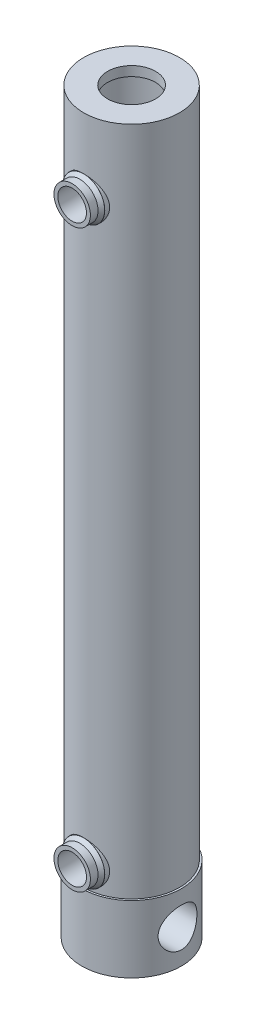
SolidWorks part; units mm, degrees
ref_plane "Plan de face" through (0, 0, 0) normal (0, 0, 1) x (1, 0, 0)
ref_plane "Plan de dessus" through (0, 0, 0) normal (0, 1, 0) x (1, 0, 0)
ref_plane "Plan de droite" through (0, 0, 0) normal (1, 0, 0) x (0, 0, -1)
sketch "Esquisse1" plane through (0, 0, 0) normal (0, 0, 1) x (1, 0, 0)
  line L0 (0, 0) -> (25, 0)
  line L1 (25, 0) -> (25, 350)
  line L2 (25, 350) -> (12.5, 350)
  line L3 (12.5, 350) -> (12.5, 345)
  line L4 (12.5, 345) -> (20, 345)
  line L5 (20, 345) -> (20, 3)
  line L6 (20, 3) -> (0, 3)
  line L7 (0, 3) -> (0, 0)
  line L8 (0, 3) -> (0, 350) construction
  line L9 (0, 350) -> (12.5, 350) construction
  dimension "D1" = 25
  dimension "D2" = 20
  dimension "D3" = 3
  dimension "D4" = 5
  dimension "D5" = 12.5
  dimension "D6" = 350
revolve "Révolution1" add sketch "Esquisse1" angle 360 about L8
sketch "Esquisse2" plane through (0, 0, 0) normal (0, -1, 0) x (-1, 0, 0)
  circle A0 centre (0, 0) radius 26
  dimension "D1" = 52
extrude "Boss.-Extru.1" add sketch "Esquisse2" along normal blind 35
sketch "Esquisse3" plane through (0, 0, 0) normal (0, 0, 1) x (1, 0, 0)
  line L0 (0, -17.5) -> (0, 0) construction
  line L1 (0, 0) -> (0, 311.5) construction
  circle A0 centre (0, -17.5) radius 10.125 construction
  circle A1 centre (0, 11.5) radius 7.475
  circle A2 centre (0, 311.5) radius 7.475
  dimension "D1" = 20.25
  dimension "D2" = 17.5
  dimension "D3" = 14.95
  dimension "D4" = 14.95
  dimension "D5" = 29
  dimension "D6" = 300
extrude "Enlèv. mat.-Extru.2" cut sketch "Esquisse3" along normal through all
sketch "Esquisse4" plane through (0, 0, 0) normal (1, 0, 0) x (0, 0, -1)
  circle A0 centre (0, -17.5) radius 10.125
  dimension "D1" = 20.25
extrude "Enlèv. mat.-Extru.3" cut sketch "Esquisse4" against normal through all both and the other way through all
ref_plane "Plan1" through (0, 0, 25) normal (0, 0, 1) x (1, 0, 0)
sketch "Esquisse5" plane through (0, 0, 25) normal (0, 0, 1) x (1, 0, 0)
  circle A0 centre (0, 311.5) radius 11
  circle A1 centre (0, 11.5) radius 11
  circle A2 centre (0, 311.5) radius 7.475
  circle A3 centre (0, 11.5) radius 7.475
  dimension "D1" = 22
  dimension "D2" = 22
extrude "Boss.-Extru.2" add sketch "Esquisse5" against normal up to next
sketch "Esquisse6" plane through (0, 0, 25) normal (0, 0, 1) x (1, 0, 0)
  circle A0 centre (0, 311.5) radius 7.475
  circle A1 centre (0, 311.5) radius 9.5
  circle A2 centre (0, 11.5) radius 7.475
  circle A3 centre (0, 11.5) radius 9.5
  dimension "D1" = 19
  dimension "D2" = 19
extrude "Boss.-Extru.3" add sketch "Esquisse6" along normal blind 6
chamfer "Chanfrein2" distance 2 angle 36 2 edges at (9.5, 311.5, 25) (9.5, 11.5, 25)
